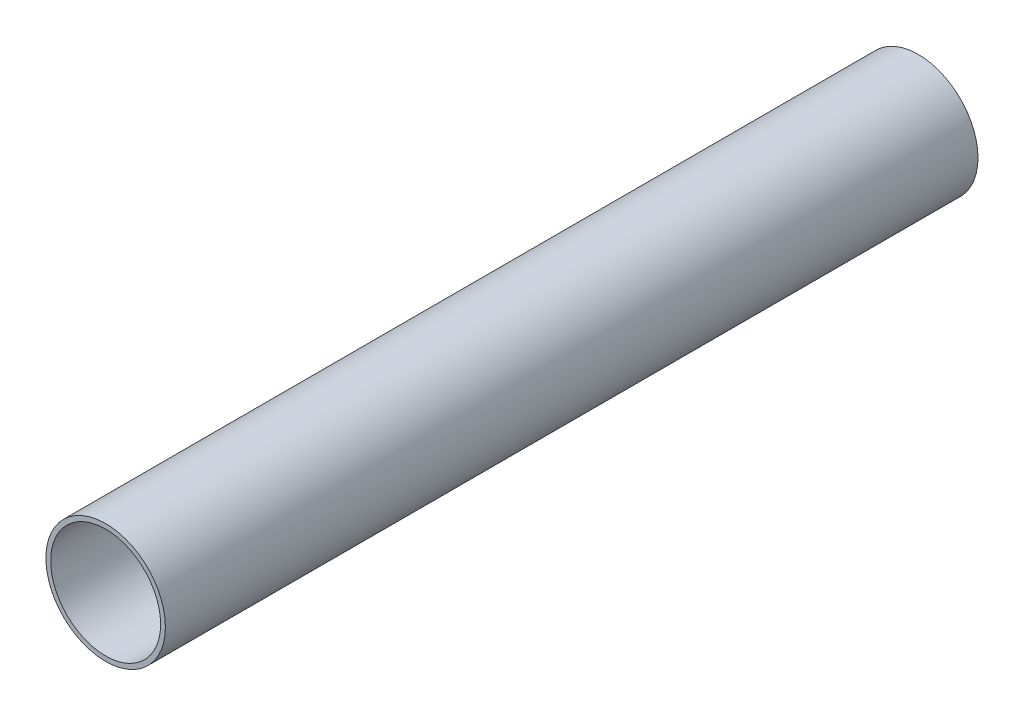
SolidWorks part; units mm, degrees
ref_plane "Front Plane" through (0, 0, 0) normal (0, 0, 1) x (1, 0, 0)
ref_plane "Top Plane" through (0, 0, 0) normal (0, 1, 0) x (1, 0, 0)
ref_plane "Right Plane" through (0, 0, 0) normal (1, 0, 0) x (0, 0, -1)
sketch "Sketch1" plane through (0, 0, 0) normal (0, 0, 1) x (1, 0, 0)
  circle A0 centre (0, 0) radius 12.5
  circle A1 centre (0, 0) radius 11.5
  dimension "D1" = 25
  dimension "D2" = 23
extrude "Boss-Extrude1" add sketch "Sketch1" along normal blind 170
